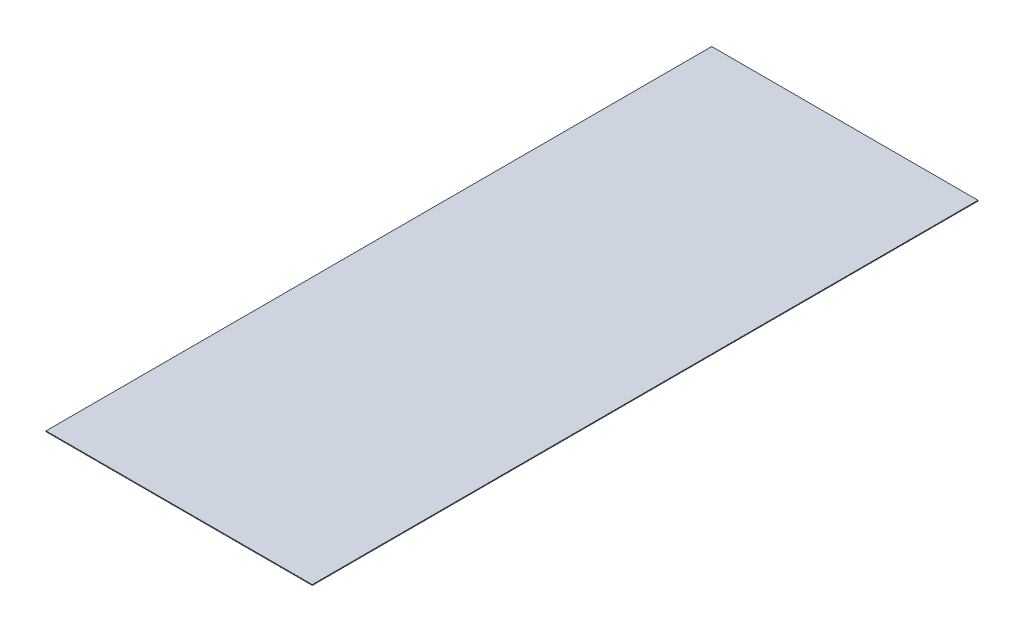
SolidWorks part; units mm, degrees
material "ASTM A36 Acero"
ref_plane "Alzado" through (0, 0, 0) normal (0, 0, 1) x (1, 0, 0)
ref_plane "Planta" through (0, 0, 0) normal (0, 1, 0) x (1, 0, 0)
ref_plane "Vista lateral" through (0, 0, 0) normal (1, 0, 0) x (0, 0, -1)
sketch "Croquis1" plane through (0, 0, 0) normal (0, 1, 0) x (1, 0, 0)
  line L1 (-609.6, -1524) -> (609.6, -1524)
  line L2 (-609.6, -1524) -> (-609.6, 1524)
  line L3 (-609.6, 1524) -> (609.6, 1524)
  line L4 (609.6, -1524) -> (609.6, 1524)
  line L5 (-609.6, -1524) -> (609.6, 1524) construction
  line L6 (-609.6, 1524) -> (609.6, -1524) construction
  point P0 (0, 0)
  dimension "D1" = 3048
  dimension "D2" = 1219.2
extrude "Saliente-Extruir1" add sketch "Croquis1" along normal blind 3.4
